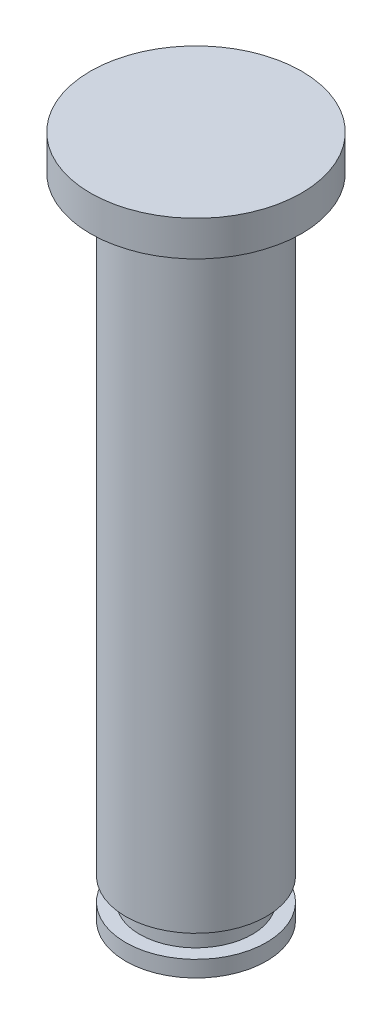
SolidWorks part; units mm, degrees
ref_plane "Front Plane" through (0, 0, 0) normal (0, 0, 1) x (1, 0, 0)
ref_plane "Top Plane" through (0, 0, 0) normal (0, 1, 0) x (1, 0, 0)
ref_plane "Right Plane" through (0, 0, 0) normal (1, 0, 0) x (0, 0, -1)
sketch "Sketch1" plane through (0, 0, 0) normal (0, 1, 0) x (1, 0, 0)
  circle A0 centre (0, 0) radius 1
extrude "Boss-Extrude1" add sketch "Sketch1" along normal blind 9.2
sketch "Sketch2" plane through (0, 9.2, 0) normal (0, 1, 0) x (1, 0, 0)
  circle A0 centre (0, 0) radius 1.5
extrude "Boss-Extrude2" add sketch "Sketch2" along normal blind 0.5
sketch "Sketch4" plane through (0, 0, 0) normal (1, 0, 0) x (0, 0, -1)
  line L1 (-1, 9.2) -> (1, 9.2) construction
  line L2 (0, 9.2) -> (0, 0.55)
  line L4 (-1, 9.2) -> (-1, 0) construction
  line L5 (-1, 0.55) -> (-1, 0.23)
  line L6 (-1, 0.23) -> (-0.8, 0.23)
  line L7 (-0.8, 0.23) -> (-0.8, 0.55)
  line L8 (-0.8, 0.55) -> (-1, 0.55)
revolve "Cut-Revolve4" cut sketch "Sketch4" angle 360 about L2
